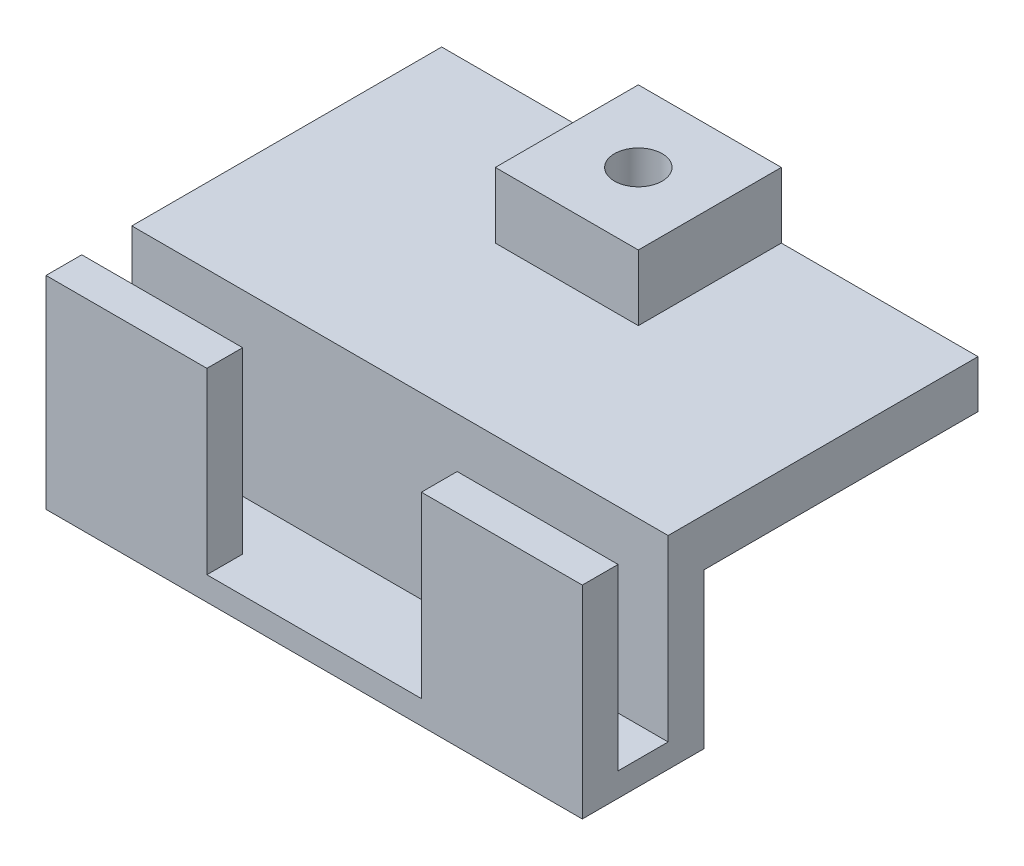
SolidWorks part; units mm, degrees
ref_plane "Ebene vorne" through (0, 0, 0) normal (0, 0, 1) x (1, 0, 0)
ref_plane "Ebene oben" through (0, 0, 0) normal (0, 1, 0) x (1, 0, 0)
ref_plane "Ebene rechts" through (0, 0, 0) normal (1, 0, 0) x (0, 0, -1)
sketch "Sketch1" plane through (0, 0, 0) normal (0, 1, 0) x (1, 0, 0)
  line L1 (-22.5, 5.1) -> (22.5, 5.1)
  line L2 (-22.5, 5.1) -> (-22.5, -5.1)
  line L3 (-22.5, -5.1) -> (22.5, -5.1)
  line L4 (22.5, 5.1) -> (22.5, -5.1)
  line L5 (-22.5, 5.1) -> (22.5, -5.1) construction
  line L6 (-22.5, -5.1) -> (22.5, 5.1) construction
  point P0 (0, 0)
  dimension "D1" = 10.2
  dimension "D2" = 45
extrude "Extrude1" add sketch "Sketch1" along normal blind 2 contours L2 L1 L4 L3
sketch "Sketch2" plane through (0, 2, 0) normal (0, 1, 0) x (1, 0, 0)
  line L0 (22.5, 5.1) -> (22.5, -5.1) construction
  line L1 (-22.5, -5.1) -> (-9, -5.1)
  line L2 (-22.5, -5.1) -> (-22.5, -2.1)
  line L3 (-22.5, -2.1) -> (-9, -2.1)
  line L4 (-9, -5.1) -> (-9, -2.1)
  line L5 (22.5, -5.1) -> (9, -5.1)
  line L6 (22.5, -5.1) -> (22.5, -2.1)
  line L7 (22.5, -2.1) -> (9, -2.1)
  line L8 (9, -5.1) -> (9, -2.1)
  line L9 (-22.5, 5.1) -> (22.5, 5.1)
  line L10 (-22.5, 5.1) -> (-22.5, 2.1)
  line L11 (-22.5, 2.1) -> (22.5, 2.1)
  line L12 (22.5, 5.1) -> (22.5, 2.1)
  dimension "D1" = 3
  dimension "D2" = 13.5
  dimension "D3" = 3
  dimension "D4" = 13.5
  dimension "D5" = 3
extrude "Extrude2" add sketch "Sketch2" along normal blind 15
sketch "Sketch3" plane through (0, 0, -5.1) normal (0, 0, -1) x (-1, 0, 0)
  line L1 (-22.5, 17) -> (22.5, 17)
  line L2 (-22.5, 17) -> (-22.5, 13)
  line L3 (-22.5, 13) -> (22.5, 13)
  line L4 (22.5, 17) -> (22.5, 13)
  line L5 (22.5, 17) -> (22.5, 0) construction
  dimension "D1" = 4
  dimension "D2" = 45
extrude "Extrude3" add sketch "Sketch3" along normal blind 23
sketch "Sketch6" plane through (0, 17, 0) normal (0, 1, 0) x (1, 0, 0)
  line L1 (-6, 16.1) -> (6, 16.1)
  line L2 (-6, 16.1) -> (-6, 28.1)
  line L3 (-6, 28.1) -> (6, 28.1)
  line L4 (6, 16.1) -> (6, 28.1)
  line L5 (-6, 16.1) -> (6, 28.1) construction
  line L6 (-6, 28.1) -> (6, 16.1) construction
  point P0 (0, 22.1)
  dimension "D1" = 12
  dimension "D2" = 12
extrude "Extrude4" add sketch "Sketch6" along normal blind 5.5
sketch "Sketch7" plane through (0, 22.5, 0) normal (0, 1, 0) x (1, 0, 0)
  line L1 (6, 28.1) -> (-6, 28.1) construction
  circle A0 centre (0, 22.1) radius 2
  dimension "D1" = 4
  dimension "D2" = 6
extrude "Extrude5" cut sketch "Sketch7" against normal blind 5.5
